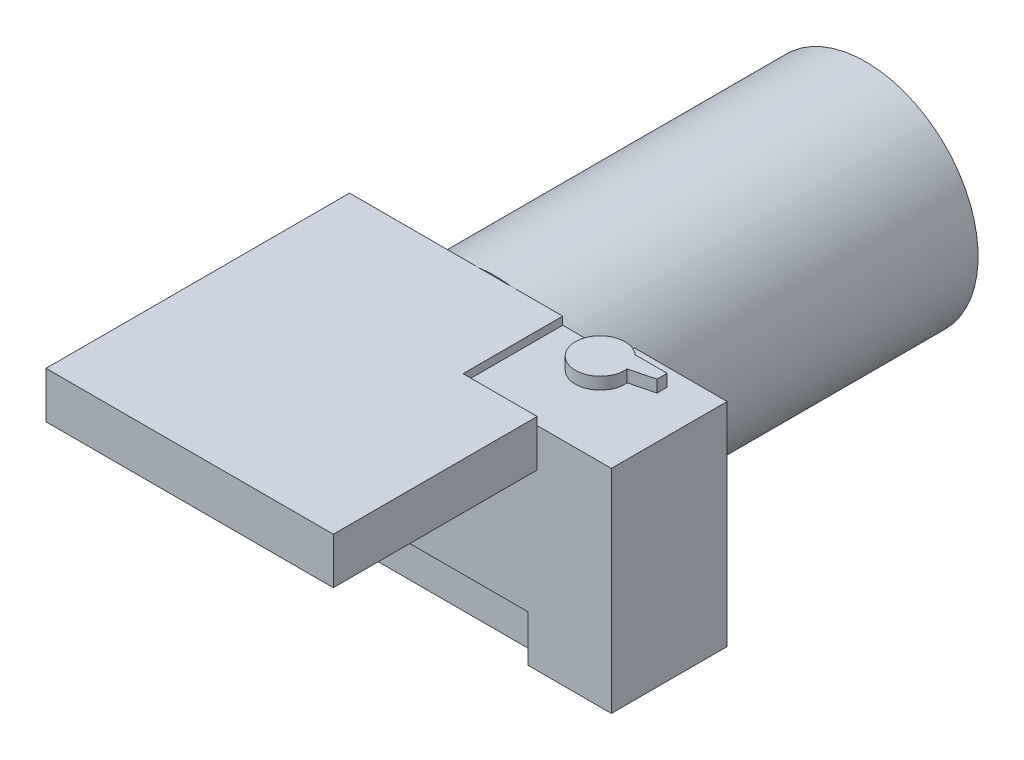
SolidWorks part; units mm, degrees
ref_plane "Front Plane" through (0, 0, 0) normal (0, 0, 1) x (1, 0, 0)
ref_plane "Top Plane" through (0, 0, 0) normal (0, 1, 0) x (1, 0, 0)
ref_plane "Right Plane" through (0, 0, 0) normal (1, 0, 0) x (0, 0, -1)
sketch "Sketch1" plane through (0, 0, 0) normal (0, 1, 0) x (1, 0, 0)
  line L1 (0, 0) -> (99.06, 0)
  line L2 (0, 0) -> (0, 27.305)
  line L3 (0, 27.305) -> (99.06, 27.305)
  line L4 (99.06, 0) -> (99.06, 27.305)
  line L5 (99.06, 27.305) -> (73.66, 27.305)
  line L6 (99.06, 27.305) -> (99.06, 31.75)
  line L7 (99.06, 31.75) -> (73.66, 31.75)
  line L8 (73.66, 27.305) -> (73.66, 31.75)
  dimension "D1" = 99.06
  dimension "D2" = 27.305
  dimension "D3" = 25.4
  dimension "D4" = 4.445
extrude "Boss-Extrude1" add sketch "Sketch1" along normal blind 58.166 contours L1 L4 L3 L2 | L8 L3 L6 L7
sketch "Sketch2" plane through (0, 0, 0) normal (0, -1, 0) x (1, 0, 0)
  line L0 (0, 0) -> (0, -27.305) construction
  line L1 (0, -27.305) -> (73.66, -27.305) construction
  circle A0 centre (39.878, -17.145) radius 3.175
  dimension "D1" = 6.35
  dimension "D2" = 39.878
  dimension "D3" = 10.16
extrude "Cut-Extrude1" cut sketch "Sketch2" against normal blind 25.4
sketch "Sketch3" plane through (0, 0, -27.305) normal (0, 0, -1) x (-1, 0, 0)
  line L0 (-39.878, 0) -> (-39.878, 55.1498) construction
  line L1 (-43.053, 0) -> (-36.703, 0)
  line L2 (-43.053, 0) -> (-36.703, 0)
  line L3 (0, 0) -> (-73.66, 0) construction
  circle A0 centre (-39.878, 29.845) radius 30.7975
  dimension "D2" = 61.595
  dimension "D3" = 29.845
  dimension "D1" = 0
extrude "Boss-Extrude2" add sketch "Sketch3" along normal blind 101.6
sketch "Sketch4" plane through (0, 0, -27.305) normal (0, 0, -1) x (-1, 0, 0)
  line L0 (0, 58.166) -> (0, 0) construction
  line L1 (0, 0) -> (-32.2779, 0) construction
  circle A0 centre (-11.938, 9.525) radius 4.064
  dimension "D1" = 8.128
  dimension "D2" = 11.938
  dimension "D3" = 9.525
extrude "Boss-Extrude3" add sketch "Sketch4" along normal blind 2.54
sketch "Sketch5" plane through (0, 58.166, 0) normal (0, 1, 0) x (1, 0, 0)
  line L0 (0, 0) -> (0, 27.305) construction
  line L1 (51.9779, 27.305) -> (73.66, 27.305) construction
  line L2 (78.6801, 26.924) -> (87.4395, 26.924)
  line L3 (87.4395, 26.924) -> (87.4395, 24.13)
  line L4 (87.4395, 24.13) -> (80.9328, 22.479)
  line L5 (74.168, 21.844) -> (53.7947, 21.844) construction
  line L6 (67.3735, 21.844) -> (67.3735, 11.7816) construction
  circle A0 centre (74.168, 21.844) radius 6.7945
  line M7 (73.66, 31.75) -> (73.66, 27.305)
  line M8 (73.66, 27.305) -> (51.9779, 27.305)
  dimension "D1" = 13.589
  dimension "D2" = 74.168
  dimension "D3" = 5.461
  dimension "D4" = 20.066
  dimension "D5" = 0.381
  dimension "D6" = 4.445
  dimension "D7" = 2.794
extrude "Boss-Extrude4" add sketch "Sketch5" along normal blind 3.302 contours A0 M7 M8 | A0 M7 M8 | A0 L4 L3 L2
sketch "Sketch6" plane through (0, 58.166, 0) normal (0, 1, 0) x (1, 0, 0)
  line L0 (51.9779, 27.305) -> (70.1254, 27.305) construction
  line L1 (0, 0) -> (58.42, 0)
  line L2 (0, 0) -> (0, 27.305)
  line L3 (0, 27.305) -> (58.42, 27.305)
  line L4 (58.42, 0) -> (58.42, 27.305)
  dimension "D1" = 58.42
extrude "Boss-Extrude5" add sketch "Sketch6" along normal blind 2.159 contours L4 L3 L2 L1
sketch "Sketch8" plane through (0, 0, 0) normal (0, -1, 0) x (1, 0, 0)
  line L1 (0, 0) -> (76.2, 0)
  line L2 (0, 0) -> (0, -4.064)
  line L3 (0, -4.064) -> (76.2, -4.064)
  line L4 (76.2, 0) -> (76.2, -4.064)
  line L5 (0, -27.305) -> (32.2779, -27.305) construction
  dimension "D1" = 23.241
  dimension "D2" = 76.2
extrude "Cut-Extrude2" cut sketch "Sketch8" against normal blind 12.7 contours L3 L4 L1 L2
sketch "Sketch9" plane through (0, 60.325, 0) normal (0, 1, 0) x (1, 0, 0)
  line L1 (0, 0) -> (78.74, 0)
  line L2 (0, 0) -> (0, -55.88)
  line L3 (0, -55.88) -> (78.74, -55.88)
  line L4 (78.74, 0) -> (78.74, -55.88)
  dimension "D1" = 55.88
  dimension "D2" = 78.74
extrude "Boss-Extrude6" add sketch "Sketch9" against normal blind 12.7
